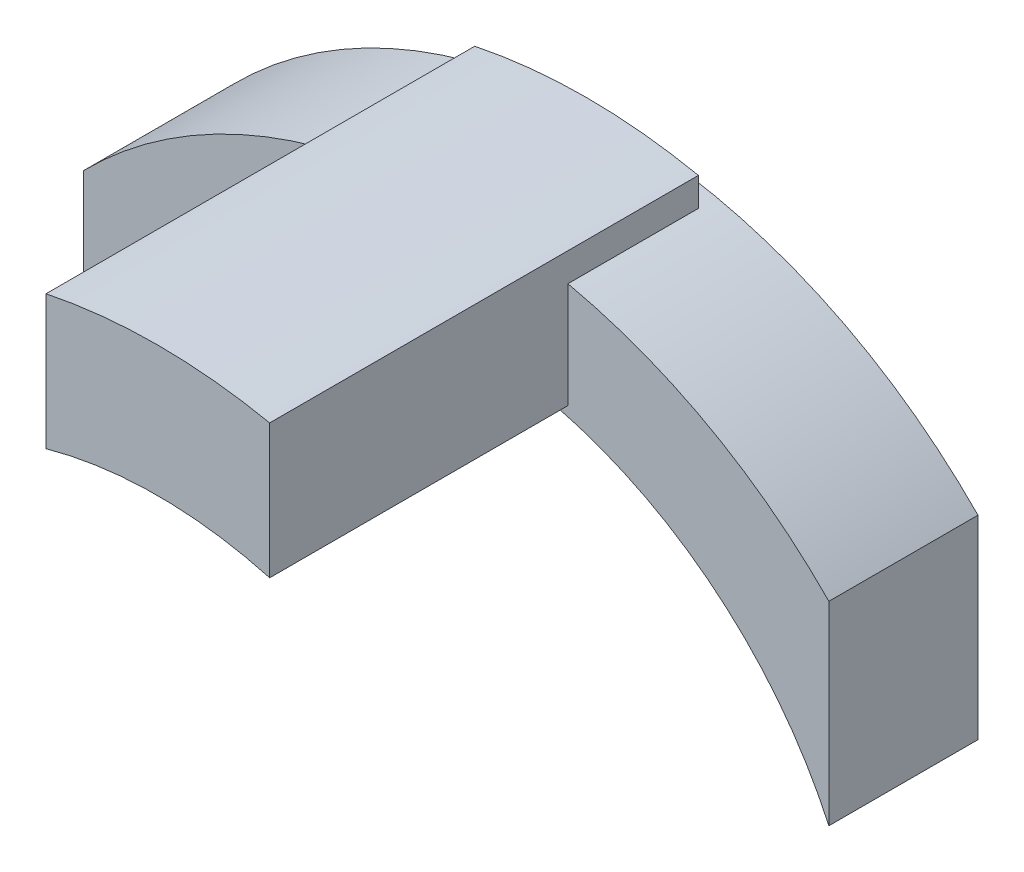
SolidWorks part; units mm, degrees
ref_plane "Front Plane" through (0, 0, 0) normal (0, 0, 1) x (1, 0, 0)
ref_plane "Top Plane" through (0, 0, 0) normal (0, 1, 0) x (1, 0, 0)
ref_plane "Right Plane" through (0, 0, 0) normal (1, 0, 0) x (0, 0, -1)
sketch "Sketch1" plane through (0, 0, 0) normal (0, 0, 1) x (1, 0, 0)
  line L0 (-20, 9.1652) -> (-20, 19.5959)
  line L1 (20, 19.5959) -> (20, 9.1652)
  arc A0 (20, 9.1652) -> (-20, 9.1652) centre (0, 0) ccw
  arc A1 (20, 19.5959) -> (-20, 19.5959) centre (0, 0) ccw
  dimension "D1" = 44
  dimension "D3" = 6
  dimension "D2" = 40
extrude "Extrude1" add sketch "Sketch1" along normal mid plane 8
sketch "Sketch2" plane through (0, 0, 4) normal (0, 0, -1) x (-1, 0, 0)
  line L0 (6, 21.6852) -> (6, 28.8834)
  line L1 (-6, 28.8834) -> (-6, 21.6852)
  arc A0 (6, 28.8834) -> (-6, 28.8834) centre (0, 0) ccw
  arc A2 (6, 21.6852) -> (-6, 21.6852) centre (0, 0) ccw
  arc A3 (20, 9.1652) -> (-20, 9.1652) centre (0, 0) ccw construction
  dimension "D2" = 7
  dimension "D3" = 0.5
  dimension "D1" = 12
extrude "Extrude2" add sketch "Sketch2" against normal blind 16 and the other way blind 7
